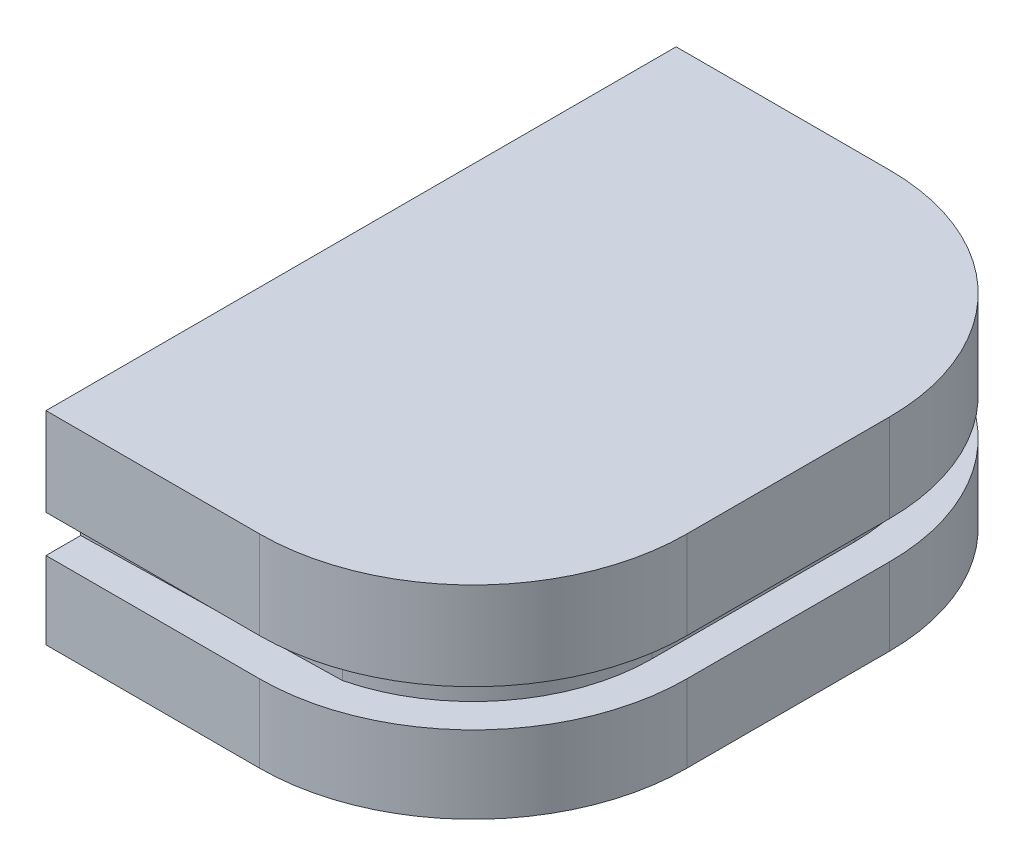
SolidWorks part; units mm, degrees
ref_plane "前基準面" through (0, 0, 0) normal (0, 0, 1) x (1, 0, 0)
ref_plane "上基準面" through (0, 0, 0) normal (0, 1, 0) x (1, 0, 0)
ref_plane "右基準面" through (0, 0, 0) normal (1, 0, 0) x (0, 0, -1)
sketch "草圖1" plane through (0, 0, 0) normal (0, 1, 0) x (1, 0, 0)
  line L1 (0, 0) -> (8, 0)
  line L2 (0, 0) -> (0, 11.8)
  line L3 (0, 11.8) -> (8, 11.8)
  line L4 (8, 0) -> (8, 11.8)
  dimension "D1" = 8
  dimension "D2" = 11.8
extrude "填料-伸長1" add sketch "草圖1" along normal blind 3.8
fillet "圓角1" radius 4 2 edges at (8, 1.9, -11.8) (8, 1.9, 0)
ref_plane "平面1" through (0, 1.8, 0) normal (0, 1, 0) x (1, 0, 0)
sketch "草圖2" plane through (0, 1.8, 0) normal (0, 1, 0) x (1, 0, 0)
  line L0 (0, 11.8) -> (0, 0) construction
  line L1 (0, 11.8) -> (0, 11.0257)
  line L2 (0, 11.0257) -> (4.904, 11.0257)
  line L3 (4, 11.8) -> (0, 11.8) construction
  line L8 (0, 0.65) -> (0, 0)
  line L9 (4, 11.8) -> (0, 11.8)
  line L10 (8, 4) -> (8, 7.8) construction
  line L11 (8, 4) -> (8, 7.8)
  line L12 (0, 0) -> (4, 0) construction
  line L13 (0, 0) -> (4, 0)
  line L14 (7.35, 7.8) -> (7.35, 4)
  line L18 (4.8028, 0.7476) -> (0, 0.65)
  line L19 (0, 11.8) -> (0, 0) construction
  arc A0 (8, 7.8) -> (4, 11.8) centre (4, 7.8) ccw construction
  arc A1 (8, 7.8) -> (4, 11.8) centre (4, 7.8) ccw
  arc A2 (4, 0) -> (8, 4) centre (4, 4) ccw construction
  arc A3 (4, 0) -> (8, 4) centre (4, 4) ccw
  arc A4 (4.904, 11.0257) -> (7.35, 7.8) centre (4, 7.8) cw
  arc A5 (7.35, 4) -> (4.8028, 0.7476) centre (4, 4) cw
  dimension "D1" = 0.65
extrude "除料-伸長1" cut sketch "草圖2" against normal mid plane 0.7
